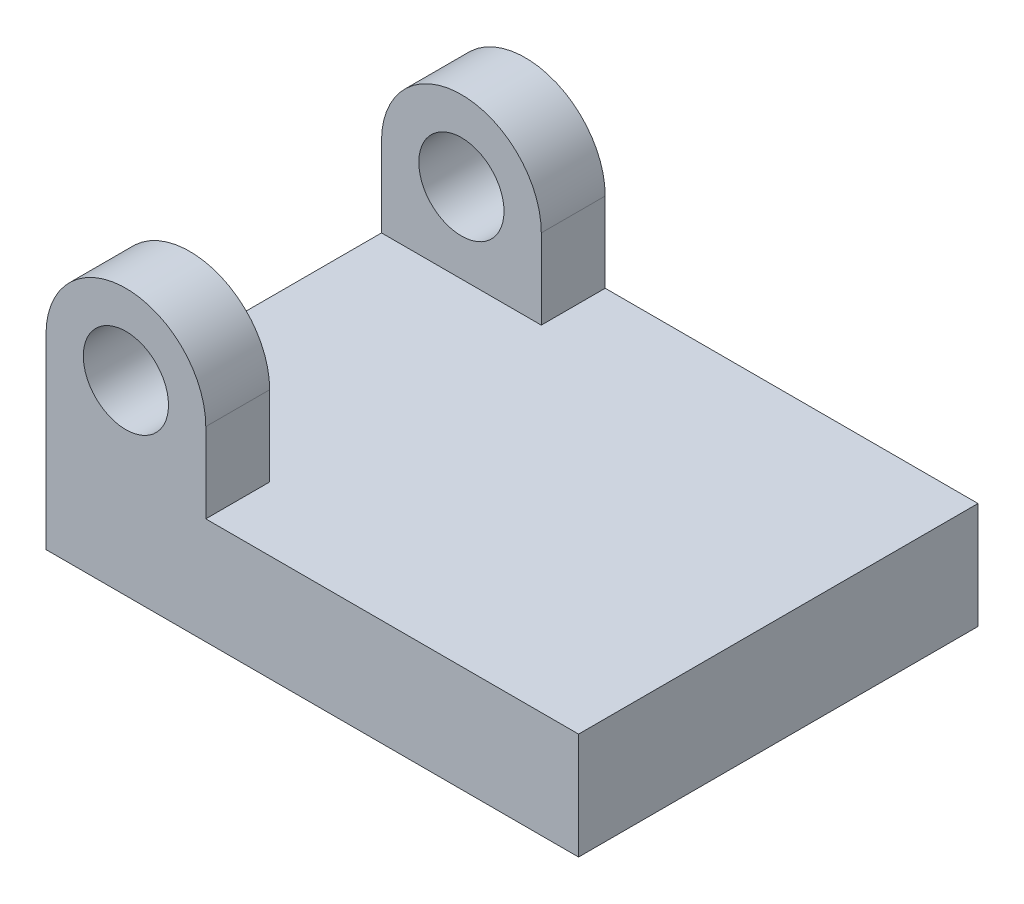
SolidWorks part; units mm, degrees
ref_plane "前视基准面" through (0, 0, 0) normal (0, 0, 1) x (1, 0, 0)
ref_plane "上视基准面" through (0, 0, 0) normal (0, 1, 0) x (1, 0, 0)
ref_plane "右视基准面" through (0, 0, 0) normal (1, 0, 0) x (0, 0, -1)
sketch "草图1" plane through (0, 0, 0) normal (0, 1, 0) x (1, 0, 0)
  line L1 (-12.3343, 6.4834) -> (7.6657, 6.4834)
  line L2 (-12.3343, 6.4834) -> (-12.3343, -8.5166)
  line L3 (-12.3343, -8.5166) -> (7.6657, -8.5166)
  line L4 (7.6657, 6.4834) -> (7.6657, -8.5166)
  dimension "D1" = 15
  dimension "D2" = 20
extrude "凸台-拉伸2" add sketch "草图1" along normal blind 4
sketch "草图3" plane through (0, 4, 0) normal (0, 1, 0) x (1, 0, 0)
  line L0 (7.6657, 6.4834) -> (-12.3343, 6.4834) construction
  line L1 (-12.3343, -8.5166) -> (-6.3343, -8.5166)
  line L2 (-12.3343, -8.5166) -> (-12.3343, 6.4834)
  line L3 (-12.3343, 6.4834) -> (-6.3343, 6.4834)
  line L4 (-6.3343, -8.5166) -> (-6.3343, 6.4834)
  dimension "D1" = 6
extrude "凸台-拉伸3" add sketch "草图3" along normal blind 6
sketch "草图4" plane through (0, 10, 0) normal (0, 1, 0) x (1, 0, 0)
  line L0 (-12.3343, 6.4834) -> (-12.3343, -8.5166) construction
  line L1 (-12.3343, 4.0834) -> (-6.3343, 4.0834)
  line L2 (-12.3343, 4.0834) -> (-12.3343, -6.1166)
  line L3 (-12.3343, -6.1166) -> (-6.3343, -6.1166)
  line L4 (-6.3343, 4.0834) -> (-6.3343, -6.1166)
  line L5 (-6.3343, -8.5166) -> (-6.3343, 6.4834) construction
  line L6 (-6.3343, 6.4834) -> (-12.3343, 6.4834) construction
  line L7 (-12.3343, -8.5166) -> (-6.3343, -8.5166) construction
  dimension "D1" = 2.4
  dimension "D2" = 2.4
extrude "切除-拉伸1" cut sketch "草图4" against normal blind 6
sketch "草图5" plane through (0, 0, 8.5166) normal (0, 0, 1) x (1, 0, 0)
  line L0 (-12.3343, 10) -> (-12.3343, 7)
  line L1 (-6.3343, 4) -> (-12.3343, 4) construction
  line L2 (-6.3343, 4) -> (-6.3343, 10) construction
  line L3 (-6.3343, 10) -> (-12.3343, 10)
  line L4 (-12.3343, 4) -> (-12.3343, 10) construction
  line L5 (-6.3343, 10) -> (-6.3343, 7)
  arc A0 (-12.3343, 7) -> (-6.3343, 7) centre (-9.3343, 7) cw
  circle A1 centre (-9.3343, 7) radius 1.6
  point P6 (-12.3343, 7)
  point P7 (-9.3343, 10)
  point P8 (-6.3343, 7)
  line M7 (-6.3343, 4) -> (-6.3343, 10)
  line M8 (-6.3343, 10) -> (-12.3343, 10)
  line M9 (-12.3343, 10) -> (-12.3343, 0)
extrude "切除-拉伸2" cut sketch "草图5" against normal blind 21 contours A1 | A0 L3 M9 | A0 M8 M7
